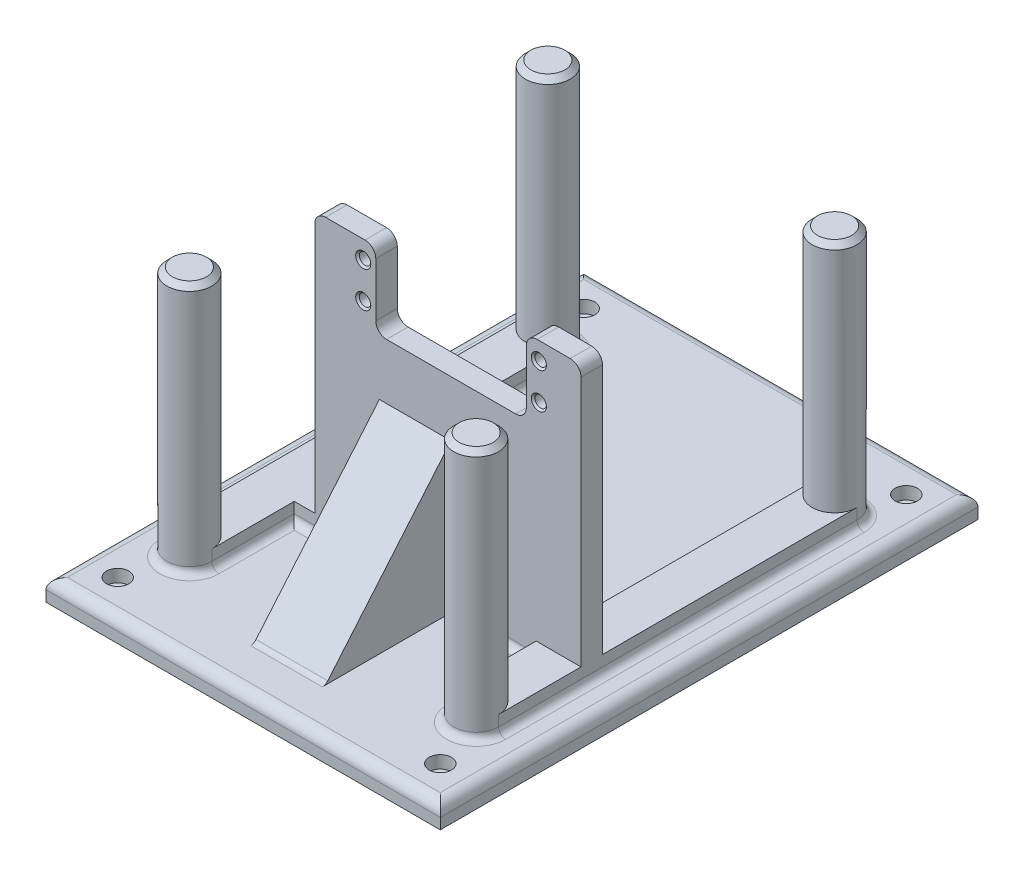
SolidWorks part; units mm, degrees
ref_plane "前视基准面" through (0, 0, 0) normal (0, 0, 1) x (1, 0, 0)
ref_plane "上视基准面" through (0, 0, 0) normal (0, 1, 0) x (1, 0, 0)
ref_plane "右视基准面" through (0, 0, 0) normal (1, 0, 0) x (0, 0, -1)
sketch "草图1" plane through (0, 0, 0) normal (0, 1, 0) x (1, 0, 0)
  line L1 (-55, 75) -> (55, 75)
  line L2 (-55, 75) -> (-55, -75)
  line L3 (-55, -75) -> (55, -75)
  line L4 (55, 75) -> (55, -75)
  line L5 (-55, 75) -> (55, -75) construction
  line L6 (-55, -75) -> (55, 75) construction
  point P0 (0, 0)
  dimension "D1" = 110
  dimension "D2" = 150
extrude "凸台-拉伸1" add sketch "草图1" along normal blind 6 contours L2 L3 L4 L1
sketch "草图2" plane through (0, 6, 0) normal (0, 1, 0) x (1, 0, 0)
  line L0 (-72.0457, 0) -> (71.4138, 0) construction
  line L1 (0, 82.6841) -> (0, -82.2628) construction
  circle A0 centre (-40, 50) radius 6.25
  circle A1 centre (40, 50) radius 6.25
  circle A2 centre (40, -50) radius 6.25
  circle A3 centre (-40, -50) radius 6.25
  dimension "D3" = 12.5
  dimension "D1" = 50
  dimension "D2" = 40
extrude "凸台-拉伸2" add sketch "草图2" along normal blind 70
sketch "草图3" plane through (0, 6, 0) normal (0, 1, 0) x (1, 0, 0)
  line L0 (-69.3072, 0) -> (70.1498, 0) construction
  line L1 (0, 82.0521) -> (0, -82.4734) construction
  circle A0 centre (-45, 65) radius 1.7
  circle A1 centre (-45, -65) radius 1.7
  circle A2 centre (45, -65) radius 1.7
  circle A3 centre (45, 65) radius 1.7
  dimension "D3" = 3.4
  dimension "D1" = 65
  dimension "D2" = 45
extrude "切除-拉伸1" cut sketch "草图3" against normal through all
sketch "草图4" plane through (0, 6, 0) normal (0, 1, 0) x (1, 0, 0)
  line L0 (-68.0432, 0) -> (70.1498, 0) construction
  line L1 (0, 79.1029) -> (0, -80.7881) construction
  circle A0 centre (-45, 65) radius 3.1
  circle A1 centre (45, 65) radius 3.1
  circle A2 centre (45, -65) radius 3.1
  circle A3 centre (-45, -65) radius 3.1
  dimension "D1" = 6.2
extrude "切除-拉伸2" cut sketch "草图4" against normal blind 3.5
sketch "草图5" plane through (0, 6, 0) normal (0, 1, 0) x (1, 0, 0)
  line L0 (-71.2031, 0) -> (71.8351, 0) construction
  line L1 (0, 80.5775) -> (0, -81.6308) construction
  line L2 (46.25, -50) -> (46.25, -27) construction
  line L3 (-28, -21) -> (46.25, -21)
  line L4 (-28, -21) -> (-28, -27)
  line L5 (-28, -27) -> (46.25, -27)
  line L6 (46.25, -21) -> (46.25, -27)
  circle A0 centre (40, -50) radius 6.25 construction
  circle A1 centre (40, -50) radius 6.25 construction
  dimension "D3" = 21
  dimension "D2" = 28
  dimension "D4" = 6
extrude "凸台-拉伸3" add sketch "草图5" along normal blind 78
sketch "草图7" plane through (0, 0, 27) normal (0, 0, 1) x (1, 0, 0)
  line L0 (10, 115.7509) -> (10, -5.6862) construction
  line L1 (-11, 84) -> (-11, 63)
  line L2 (-28, 84) -> (46.25, 84) construction
  line L3 (-11, 63) -> (31, 63)
  line L4 (31, 84) -> (31, 63)
  line L5 (-11, 84) -> (31, 84)
  line L6 (-13.4779, 74) -> (32.972, 74) construction
  circle A0 centre (-14.5, 69) radius 1.6
  circle A1 centre (-14.5, 79) radius 1.6
  circle A2 centre (34.5, 69) radius 1.6
  circle A3 centre (34.5, 79) radius 1.6
  point P16 (10, 63)
  dimension "D3" = 10
  dimension "D6" = 49
  dimension "D4" = 3.2
  dimension "D5" = 10
  dimension "D1" = 21
  dimension "D2" = 21
extrude "切除-拉伸8" cut sketch "草图7" against normal blind 7 and the other way blind 5
sketch "草图10" plane through (0, 6, 0) normal (0, 1, 0) x (1, 0, 0)
  line L0 (-33.75, -27) -> (-33.75, -50)
  line L1 (-46.25, 50) -> (-33.75, 50)
  line L2 (-46.25, 50) -> (-46.25, -50)
  line L3 (-46.25, -50) -> (-33.75, -50)
  line L4 (-33.75, 50) -> (-33.75, -21)
  line L5 (33.75, 50) -> (46.25, 50)
  line L6 (33.75, 50) -> (33.75, -50)
  line L7 (33.75, -50) -> (46.25, -50)
  line L9 (-28, -21) -> (-33.75, -21)
  line L10 (-28, -21) -> (-28, -27)
  line L11 (-28, -27) -> (-33.75, -27)
  line L12 (-46.25, -22.5) -> (-46.25, -28.5)
  line L23 (46.25, 50) -> (46.25, -50)
  circle A0 centre (-40, 50) radius 6.25 construction
  circle A1 centre (-40, 50) radius 6.25 construction
  circle A2 centre (-40, -50) radius 6.25 construction
  circle A3 centre (-40, -50) radius 6.25 construction
  circle A4 centre (40, 50) radius 6.25 construction
  circle A5 centre (40, 50) radius 6.25 construction
  circle A6 centre (40, -50) radius 6.25 construction
extrude "凸台-拉伸4" add sketch "草图10" along normal blind 5
sketch "草图8" plane through (0, 0, 0) normal (1, 0, 0) x (0, 0, -1)
  line L0 (-27, 47.5) -> (-62, 6)
  line L1 (-27, 84) -> (-27, 11) construction
  line L2 (75, 6) -> (-75, 6) construction
  dimension "D1" = 35
rib "筋3" sketch "草图8" sketch "草图8" thickness 20 extrusion direction parallel to sketch draft on no parameters "D1"=20
fillet "圆角5" radius 2 14 edges at (33.75, 6, 38.5) (40, 6, 56.25) (46.25, 6, 0) (40, 6, -56.25) (-33.75, 6, -14.5) (-40, 6, -56.25) (-33.75, 6, 38.5) (-40, 6, 56.25) (33.75, 6, -14.5) (-46.25, 6, 0) (0, 6, 62) (21.875, 6, 27) (-21.875, 6, 27) (0, 6, 21)
fillet "圆角4" radius 3 10 edges at (-55, 6, 0) (0, 6, -75) (55, 6, 0) (0, 6, 75) (-28, 84, 24) (-11, 84, 24) (-11, 63, 24) (31, 63, 24) (31, 84, 24) (46.25, 84, 24)
chamfer "倒角1" distance 1.5 angle 45 4 edges at (40, 76, 56.25) (40, 76, -56.25) (-40, 76, -43.75) (-40, 76, 43.75)
chamfer "倒角2" distance 0.5 angle 45 8 edges at (36.1, 69, 21) (36.1, 79, 21) (-12.9, 69, 21) (-12.9, 79, 21) (32.9, 69, 27) (32.9, 79, 27) (-16.1, 69, 27) (-16.1, 79, 27)
